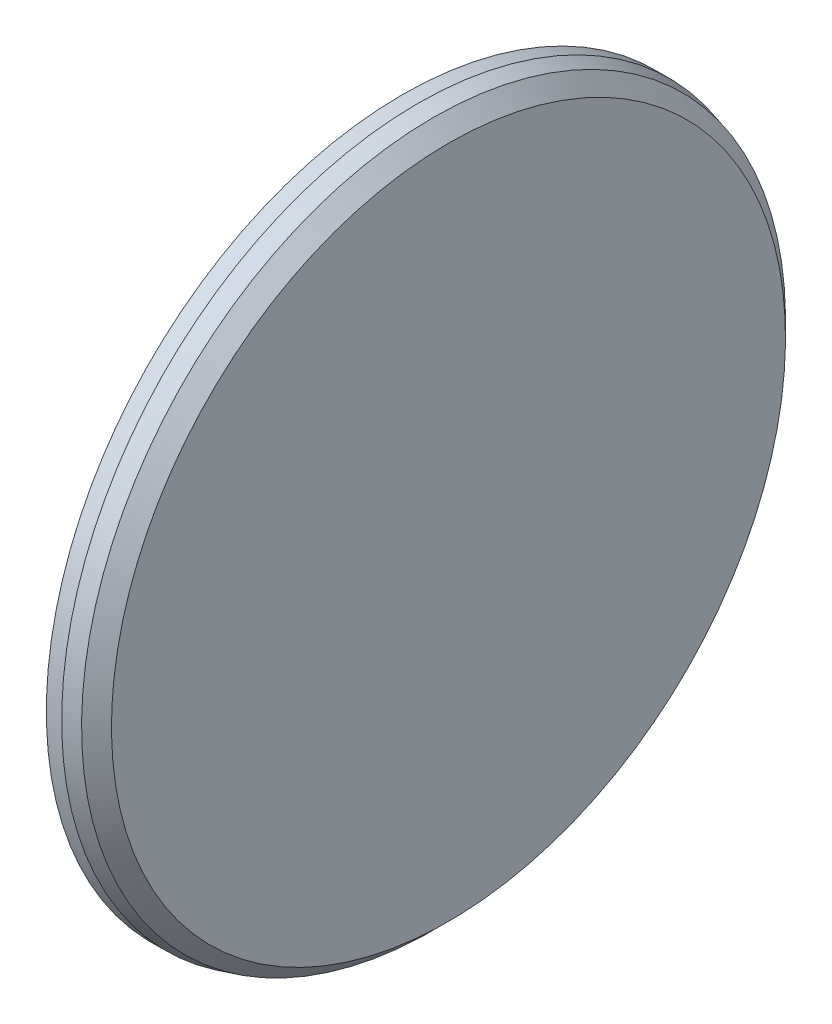
SolidWorks part; units mm, degrees
material "1060 Alloy"
ref_plane "Front Plane" through (0, 0, 0) normal (0, 0, 1) x (1, 0, 0)
ref_plane "Top Plane" through (0, 0, 0) normal (0, 1, 0) x (1, 0, 0)
ref_plane "Right Plane" through (0, 0, 0) normal (1, 0, 0) x (0, 0, -1)
sketch "Sketch1" plane through (0, 0, 0) normal (0, 0, 1) x (1, 0, 0)
  line L0 (30, 0) -> (-74.1418, 0) construction
  line L1 (-50, 0) -> (-50, 100)
  line L2 (-50, 100) -> (0, 100)
  line L3 (0, 100) -> (0, 420)
  line L4 (0, 420) -> (-30, 420)
  line L5 (-30, 420) -> (-30, 465)
  line L6 (-30, 465) -> (-10, 465)
  line L7 (-10, 465) -> (10.4904, 459.5096)
  line L8 (10.4904, 459.5096) -> (30, 440)
  line L9 (30, 440) -> (30, 0)
  line L10 (-30, 465) -> (19.3959, 465) construction
  line L11 (30, 0) -> (-50, 0)
  point P7 (0, 260)
  dimension "D2" = 200
  dimension "D3" = 30
  dimension "D4" = 60
  dimension "D5" = 80
  dimension "D6" = 880
  dimension "D7" = 20
  dimension "D8" = 15
  dimension "D9" = 45
  dimension "D10" = 45
  dimension "D11" = 930
revolve "Revolve1" add sketch "Sketch1" angle 360 about L11
sketch "Sketch2" plane through (0, 0, 0) normal (-1, 0, 0) x (0, 0, 1)
  line L0 (0, 0) -> (0, 420) construction
  line L1 (20, 105.8301) -> (20, 408.901)
  line L2 (-20, 105.8301) -> (-20, 350.9986)
  line L3 (20, 0) -> (20, 420) construction
  line L4 (-20, 0) -> (-20, 420) construction
  line L5 (465, 0) -> (-465, 0) construction
  circle A0 centre (0, 0) radius 420 construction
  circle A3 centre (0, 0) radius 465 construction
  arc A4 (27.2727, 96.2091) -> (-27.2727, 96.2091) centre (0, 0) ccw
  arc A5 (30.7317, 418.8742) -> (-93.3333, 409.4983) centre (0, 0) ccw
  arc A6 (-19.8817, 419.5292) -> (-93.3333, 409.4983) centre (0, 0) ccw
  arc A7 (-93.3333, 409.4983) -> (-20, 350.9986) centre (-80, 350.9986) cw
  arc A8 (20, 408.901) -> (30.7317, 418.8742) centre (30, 408.901) cw
  arc A9 (-20, 105.8301) -> (-27.2727, 96.2091) centre (-30, 105.8301) cw
  arc A10 (27.2727, 96.2091) -> (20, 105.8301) centre (30, 105.8301) cw
  arc A11 (-420, 0) -> (420, 0) centre (0, 0) ccw
  arc A12 (-420, 0) -> (420, 0) centre (0, 0) ccw
  point P28 (-20, 97.9796)
  circle M4 centre (0, 0) radius 100
  circle M5 centre (0, 0) radius 420
  dimension "D3" = 60
  dimension "D4" = 10
  dimension "D5" = 10
  dimension "D6" = 10
  dimension "D1" = 20
  dimension "D2" = 20
extrude "Boss-Extrude1" add sketch "Sketch2" along normal offset from surface (20 mm away) 10 contours A10 L1 A8 A5 A7 L2 A9 M4 M5 up to face at (-30, 420, 0)
pattern_circular "CirPattern1" count 9 over 360 about axis through (0, 0, 0) along (1, 0, 0) of "Boss-Extrude1"
equation "\"A\"= 60"
equation "\"B\"= 930"
equation "\"D11@Sketch1\"= \"B\""
equation "\"D4@Sketch1\"= \"A\""
